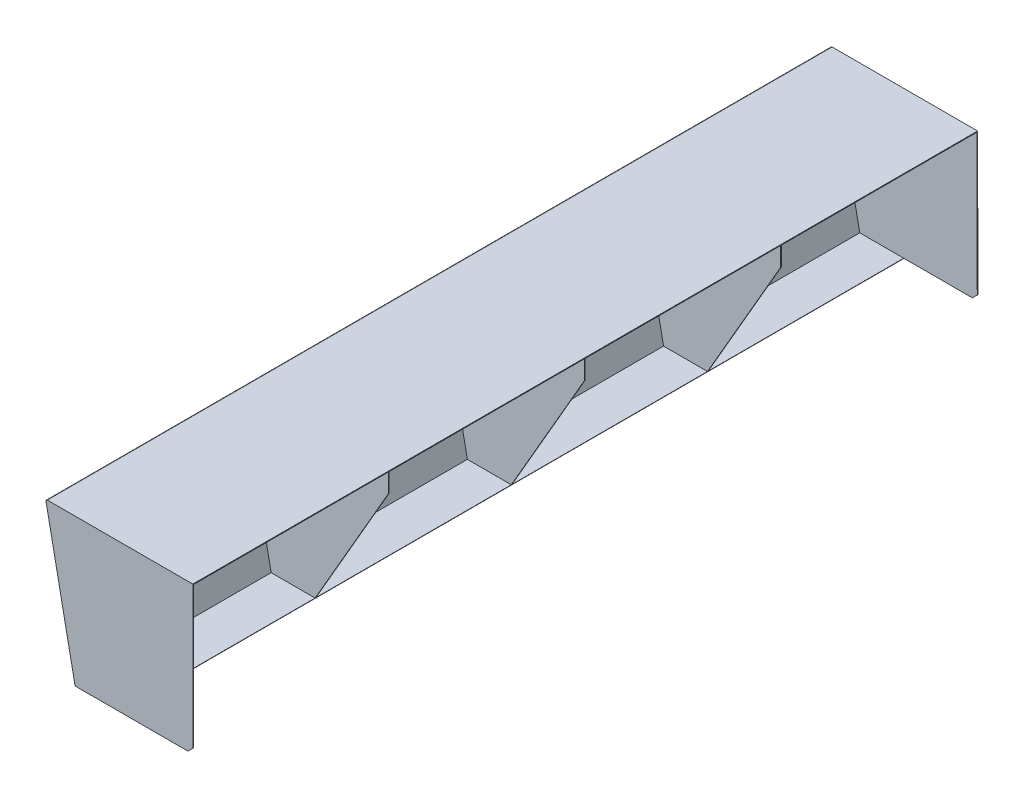
SolidWorks part; units mm, degrees
material "Q235"
ref_plane "前视基准面" through (0, 0, 0) normal (0, 0, 1) x (1, 0, 0)
ref_plane "上视基准面" through (0, 0, 0) normal (0, 1, 0) x (1, 0, 0)
ref_plane "右视基准面" through (0, 0, 0) normal (1, 0, 0) x (0, 0, -1)
sketch "草图1" plane through (0, 0, 0) normal (0, 0, 1) x (1, 0, 0)
  line L1 (0, 0) -> (300, 0)
  line L2 (0, 0) -> (0, 300)
  line L3 (0, 300) -> (300, 300)
  line L4 (300, 0) -> (300, 300)
  dimension "D1" = 300
  dimension "D2" = 300
extrude "凸台-拉伸1" add sketch "草图1" along normal blind 1600
sketch "草图7" plane through (0, 0, 1600) normal (0, 0, 1) x (1, 0, 0)
  line L0 (300, 260) -> (150, 0)
  line L1 (0, 0) -> (300, 0) construction
  line L2 (150, 0) -> (300, 0)
  line L3 (300, 0) -> (300, 260)
  line L4 (300, 0) -> (300, 300) construction
  line L5 (300, 300) -> (0, 300) construction
  dimension "D1" = 150
  dimension "D2" = 40
extrude "切除-拉伸1" cut sketch "草图7" against normal through all
sketch "草图11" plane through (0, 0, 1600) normal (0, 0, 1) x (1, 0, 0)
  line L0 (0, 300) -> (0, 0)
  line L1 (0, 0) -> (60, 0)
  line L2 (0, 0) -> (150, 0) construction
  line L3 (60, 0) -> (0, 300)
  dimension "D1" = 60
extrude "切除-拉伸4" cut sketch "草图11" against normal through all
shell "抽壳2" thickness 1.5
ref_plane "基准面1" through (0, 0, 1200) normal (0, 0, 1) x (1, 0, 0)
sketch "草图13" plane through (0, 0, 1200) normal (0, 0, 1) x (1, 0, 0)
  line L11 (1.8297, 298.5) -> (61.2297, 1.5)
  line L12 (61.2297, 1.5) -> (150.8654, 1.5)
  line L13 (150.8654, 1.5) -> (300, 260)
  line L14 (300, 260) -> (300, 298.5)
  line L15 (300, 298.5) -> (1.8297, 298.5)
  line L16 (1.8297, 298.5) -> (61.2297, 1.5)
  line L17 (61.2297, 1.5) -> (150.8654, 1.5)
  line L18 (150.8654, 1.5) -> (300, 260)
  line L19 (300, 260) -> (300, 298.5)
  line L20 (300, 298.5) -> (1.8297, 298.5)
  dimension "D1" = 0
extrude "凸台-拉伸2" add sketch "草图13" along normal blind 1.5
pattern_linear "阵列(线性)1" count 3 spacing 400 along (0, 0, -1) of "凸台-拉伸2"
sketch "草图14" plane through (0, 0, 1600) normal (0, 0, 1) x (1, 0, 0)
  line L0 (300, 260) -> (300, 10)
  line L1 (290, 0) -> (150, 0)
  line L2 (300, 260) -> (150, 0) construction
  line L3 (300, 260) -> (150, 0)
  line L4 (300, 10) -> (290, 0)
  point P1 (300, 0)
extrude "凸台-拉伸3" add sketch "草图14" against normal blind 1.5
sketch "草图15" plane through (0, 0, 0) normal (0, 0, -1) x (-1, 0, 0)
  line L0 (-300, 260) -> (-150.8654, 1.5)
  line L1 (-150.8654, 1.5) -> (-290.8654, 1.5)
  line L2 (-300.8319, 11.4999) -> (-300, 260)
  line L3 (-290.8654, 1.5) -> (-300.8319, 11.4999)
  point P5 (-300.8654, 1.5)
  dimension "D1" = 150
extrude "凸台-拉伸4" add sketch "草图15" against normal blind 1.5 contours L2 L0 L1 L3
fillet "圆角1" radius 3 1 edges at (0, 300, 800)
